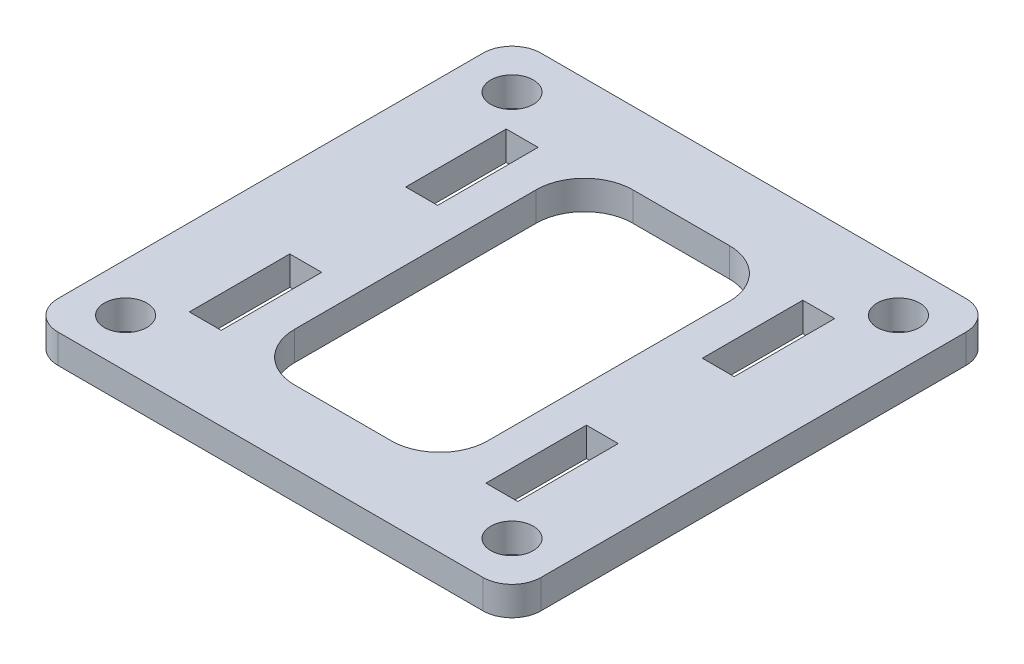
SolidWorks part; units mm, degrees
ref_plane "前视基准面" through (0, 0, 0) normal (0, 0, 1) x (1, 0, 0)
ref_plane "上视基准面" through (0, 0, 0) normal (0, 1, 0) x (1, 0, 0)
ref_plane "右视基准面" through (0, 0, 0) normal (1, 0, 0) x (0, 0, -1)
other "Configuration Table"
sketch "草图1" plane through (0, 0, 0) normal (0, 1, 0) x (1, 0, 0)
  line L0 (-15.0378, 0) -> (18.9315, 0) construction
  line L1 (-25, 25) -> (25, 25)
  line L2 (-25, 25) -> (-25, -25)
  line L3 (-25, -25) -> (25, -25)
  line L4 (25, 25) -> (25, -25)
  line L5 (-25, 25) -> (25, -25) construction
  line L6 (-25, -25) -> (25, 25) construction
  line L11 (13.7, 16.4) -> (17, 16.4)
  line L12 (13.7, 16.4) -> (13.7, 6)
  line L13 (13.7, 6) -> (17, 6)
  line L14 (17, 16.4) -> (17, 6)
  line L15 (13.7, -6) -> (17, -6)
  line L16 (17, -16.4) -> (17, -6)
  line L17 (13.7, -16.4) -> (17, -16.4)
  line L18 (13.7, -16.4) -> (13.7, -6)
  line L19 (0, 15.5748) -> (0, -14.7692) construction
  line L20 (-13.7, -16.4) -> (-13.7, -6)
  line L21 (-13.7, -16.4) -> (-17, -16.4)
  line L22 (-17, -16.4) -> (-17, -6)
  line L23 (-13.7, -6) -> (-17, -6)
  line L24 (-13.7, 6) -> (-17, 6)
  line L25 (-17, 16.4) -> (-17, 6)
  line L26 (-13.7, 16.4) -> (-17, 16.4)
  line L27 (-13.7, 16.4) -> (-13.7, 6)
  point P0 (0, 0)
  dimension "D1" = 50
  dimension "D2" = 50
  dimension "D3" = 3.3
  dimension "D4" = 10.4
  dimension "D5" = 8
  dimension "D6" = 6
extrude "凸台-拉伸1" add sketch "草图1" along normal blind 3
sketch "草图2" plane through (0, 3, 0) normal (0, 1, 0) x (1, 0, 0)
  line L1 (-10, 17.5) -> (10, 17.5)
  line L2 (-10, 17.5) -> (-10, -17.5)
  line L3 (-10, -17.5) -> (10, -17.5)
  line L4 (10, 17.5) -> (10, -17.5)
  line L5 (-10, 17.5) -> (10, -17.5) construction
  line L6 (-10, -17.5) -> (10, 17.5) construction
  point P0 (0, 0)
  dimension "D1" = 20
  dimension "D2" = 35
extrude "切除-拉伸1" cut sketch "草图2" against normal blind 3
fillet "圆角1" radius 5 4 edges at (10, 1.5, -17.5) (10, 1.5, 17.5) (-10, 1.5, 17.5) (-10, 1.5, -17.5)
sketch "草图3" plane through (0, 3, 0) normal (0, 1, 0) x (1, 0, 0)
  line L1 (-20, 20) -> (20, 20) construction
  line L2 (-20, 20) -> (-20, -20) construction
  line L3 (-20, -20) -> (20, -20) construction
  line L4 (20, 20) -> (20, -20) construction
  line L5 (-20, 20) -> (20, -20) construction
  line L6 (-20, -20) -> (20, 20) construction
  circle A0 centre (-20, 20) radius 2.2
  circle A1 centre (20, 20) radius 2.2
  circle A2 centre (20, -20) radius 2.2
  circle A3 centre (-20, -20) radius 2.2
  point P0 (0, 0)
  point P16 (0, 0)
  dimension "D3" = 4.4
  dimension "D5" = 40
  dimension "D6" = 20
  dimension "D1" = 40
  dimension "D2" = 40
  dimension "D4" = 4
extrude "切除-拉伸2" cut sketch "草图3" against normal blind 3
fillet "圆角2" radius 3 4 edges at (-25, 1.5, 25) (25, 1.5, 25) (25, 1.5, -25) (-25, 1.5, -25)
